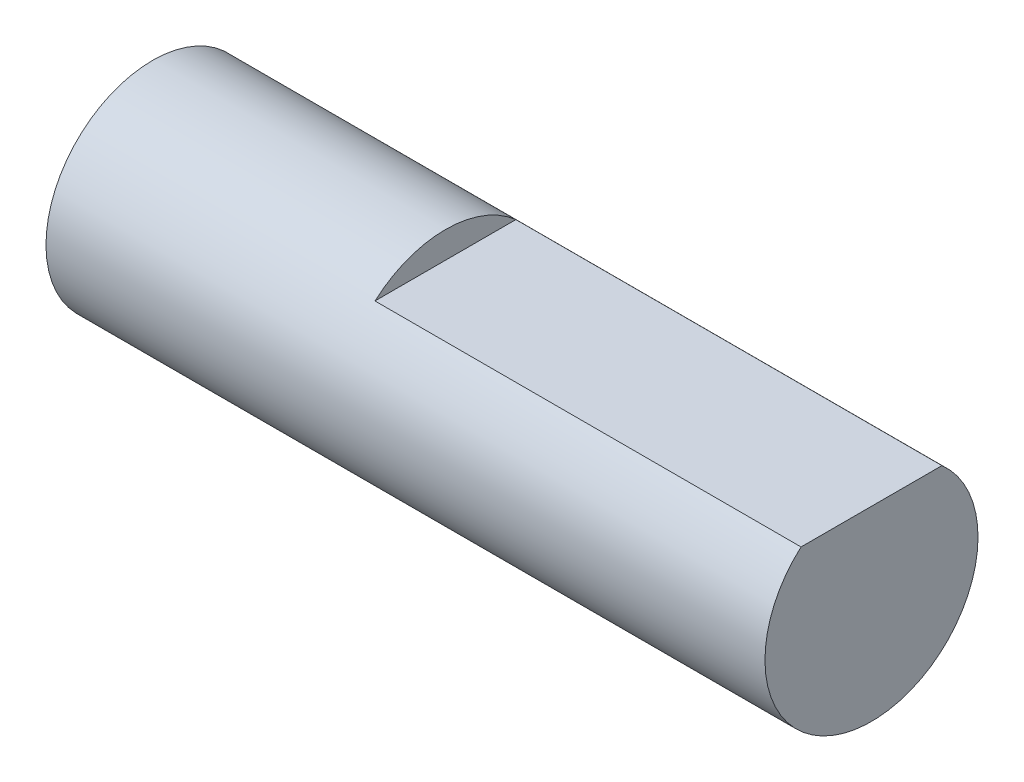
SolidWorks part; units mm, degrees
material "Alloy Steel"
ref_plane "Front Plane" through (0, 0, 0) normal (0, 0, 1) x (1, 0, 0)
ref_plane "Top Plane" through (0, 0, 0) normal (0, 1, 0) x (1, 0, 0)
ref_plane "Right Plane" through (0, 0, 0) normal (1, 0, 0) x (0, 0, -1)
sketch "Sketch1" plane through (0, 0, 0) normal (1, 0, 0) x (0, 0, -1)
  circle A0 centre (0, 0) radius 4
  dimension "D1" = 8
extrude "Boss-Extrude1" add sketch "Sketch1" along normal blind 27
sketch "Sketch3" plane through (27, 0, 0) normal (1, 0, 0) x (0, 0, -1)
  line L0 (-2.6458, 3) -> (2.6458, 3)
  circle A1 centre (0, 0) radius 4 construction
  dimension "D1" = 3
extrude "Cut-Extrude1" cut sketch "Sketch3" against normal blind 16 and the other way through all
